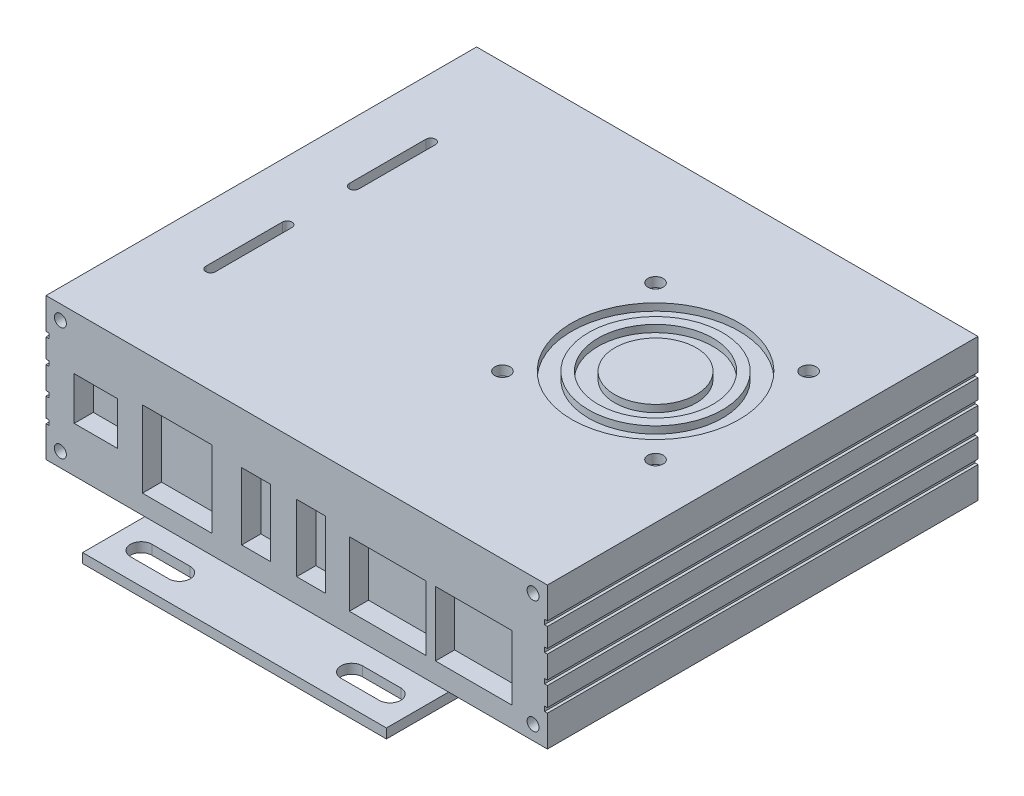
SolidWorks part; units mm, degrees
material "1060 Alloy"
ref_plane "Front Plane" through (0, 0, 0) normal (0, 0, 1) x (1, 0, 0)
ref_plane "Top Plane" through (0, 0, 0) normal (0, 1, 0) x (1, 0, 0)
ref_plane "Right Plane" through (0, 0, 0) normal (1, 0, 0) x (0, 0, -1)
sketch "Sketch1" plane through (0, 0, 0) normal (0, 1, 0) x (1, 0, 0)
  line L0 (-52.4, 45) -> (52.4, 45)
  line L1 (52.4, 45) -> (52.4, -45)
  line L2 (52.4, -45) -> (-52.4, -45)
  line L3 (-52.4, -45) -> (-52.4, 45)
extrude "Boss-Extrude1" add sketch "Sketch1" along normal blind 29.7
sketch "Sketch2" plane through (0, 0, 0) normal (0, 1, 0) x (1, 0, 0)
  line L0 (-31.75, 58) -> (31.75, 58)
  line L1 (31.75, 58) -> (31.75, -58)
  line L2 (31.75, -58) -> (-31.75, -58)
  line L3 (-31.75, -58) -> (-31.75, 58)
extrude "Boss-Extrude2" add sketch "Sketch2" against normal blind 2
sketch "Sketch3" plane through (0, -2, 0) normal (0, -1, 0) x (1, 0, 0)
  line L0 (18, 53.75) -> (26, 53.75)
  line L1 (18, 49.25) -> (26, 49.25)
  line L2 (-26, 53.75) -> (-18, 53.75)
  line L3 (-26, 49.25) -> (-18, 49.25)
  line L4 (18, -49.25) -> (26, -49.25)
  line L5 (18, -53.75) -> (26, -53.75)
  line L6 (-26, -49.25) -> (-18, -49.25)
  line L7 (-26, -53.75) -> (-18, -53.75)
  arc A0 (26, 53.75) -> (26, 49.25) centre (26, 51.5) cw
  arc A1 (18, 49.25) -> (18, 53.75) centre (18, 51.5) cw
  arc A2 (-18, 53.75) -> (-18, 49.25) centre (-18, 51.5) cw
  arc A3 (-26, 49.25) -> (-26, 53.75) centre (-26, 51.5) cw
  arc A4 (26, -49.25) -> (26, -53.75) centre (26, -51.5) cw
  arc A5 (18, -53.75) -> (18, -49.25) centre (18, -51.5) cw
  arc A6 (-18, -49.25) -> (-18, -53.75) centre (-18, -51.5) cw
  arc A7 (-26, -53.75) -> (-26, -49.25) centre (-26, -51.5) cw
extrude "Cut-Extrude1" cut sketch "Sketch3" against normal blind 3
ref_plane "Plane1" through (0, 0, 45) normal (0, 0, 1) x (1, 0, 0)
sketch "Sketch4" plane through (0, 0, 45) normal (0, 0, 1) x (1, 0, 0)
  line L0 (-46.5, 9.5) -> (-37.5, 9.5)
  line L1 (-37.5, 9.5) -> (-37.5, 18.5)
  line L2 (-37.5, 18.5) -> (-46.5, 18.5)
  line L3 (-46.5, 18.5) -> (-46.5, 9.5)
  line L4 (-32.25, 4) -> (-17.75, 4)
  line L5 (-17.75, 4) -> (-17.75, 20)
  line L6 (-17.75, 20) -> (-32.25, 20)
  line L7 (-32.25, 20) -> (-32.25, 4)
  line L8 (-11.5, 5) -> (-5.5, 5)
  line L9 (-5.5, 5) -> (-5.5, 19)
  line L10 (-5.5, 19) -> (-11.5, 19)
  line L11 (-11.5, 19) -> (-11.5, 5)
  line L12 (0, 5) -> (6, 5)
  line L13 (6, 5) -> (6, 19)
  line L14 (6, 19) -> (0, 19)
  line L15 (0, 19) -> (0, 5)
  line L16 (11, 4.25) -> (27, 4.25)
  line L17 (27, 4.25) -> (27, 17.75)
  line L18 (27, 17.75) -> (11, 17.75)
  line L19 (11, 17.75) -> (11, 4.25)
  line L20 (29, 4.25) -> (45, 4.25)
  line L21 (45, 4.25) -> (45, 17.75)
  line L22 (45, 17.75) -> (29, 17.75)
  line L23 (29, 17.75) -> (29, 4.25)
  circle A0 centre (49.4, 3) radius 1.25
  circle A1 centre (49.4, 26.7) radius 1.25
  circle A2 centre (-49.4, 3) radius 1.25
  circle A3 centre (-49.4, 26.7) radius 1.25
extrude "Cut-Extrude2" cut sketch "Sketch4" against normal blind 4
ref_plane "Plane3" through (0, 0, -45) normal (0, 0, 1) x (1, 0, 0)
sketch "Sketch5" plane through (0, 0, -45) normal (0, 0, 1) x (1, 0, 0)
  circle A0 centre (49.4, 3) radius 1.25
  circle A1 centre (49.4, 26.7) radius 1.25
  circle A2 centre (-49.4, 3) radius 1.25
  circle A3 centre (-49.4, 26.7) radius 1.25
extrude "Cut-Extrude4" cut sketch "Sketch5" along normal blind 2
ref_plane "Plane4" through (0, 29.7, 0) normal (0, 1, 0) x (1, 0, 0)
sketch "Sketch6" plane through (0, 29.7, 0) normal (0, 1, 0) x (1, 0, 0)
  circle A0 centre (25, 5) radius 17.5
  circle A1 centre (25, 5) radius 14
extrude "Cut-Extrude5" cut sketch "Sketch6" against normal blind 1.5
ref_plane "Plane5" through (0, 29.7, 0) normal (0, 1, 0) x (1, 0, 0)
sketch "Sketch7" plane through (0, 29.7, 0) normal (0, 1, 0) x (1, 0, 0)
  circle A0 centre (25, 5) radius 12
  circle A1 centre (25, 5) radius 8.5
extrude "Cut-Extrude6" cut sketch "Sketch7" against normal blind 1.5
ref_plane "Plane6" through (0, 29.7, 0) normal (0, 1, 0) x (1, 0, 0)
sketch "Sketch8" plane through (0, 29.7, 0) normal (0, 1, 0) x (1, 0, 0)
  line L0 (-39, -7) -> (-39, -23)
  line L1 (-41, -7) -> (-41, -23)
  line L2 (-39, 23) -> (-39, 7)
  line L3 (-41, 23) -> (-41, 7)
  circle A0 centre (41, -11) radius 1.6
  circle A1 centre (41, 21) radius 1.6
  circle A2 centre (9, -11) radius 1.6
  circle A3 centre (9, 21) radius 1.6
  arc A4 (-39, -23) -> (-41, -23) centre (-40, -23) cw
  arc A5 (-41, -7) -> (-39, -7) centre (-40, -7) cw
  arc A6 (-39, 7) -> (-41, 7) centre (-40, 7) cw
  arc A7 (-41, 23) -> (-39, 23) centre (-40, 23) cw
extrude "Cut-Extrude7" cut sketch "Sketch8" against normal blind 2
ref_plane "Plane7" through (52.4, 0, 0) normal (1, 0, 0) x (0, 0, -1)
sketch "Sketch9" plane through (52.4, 0, 0) normal (1, 0, 0) x (0, 0, -1)
  line L0 (45, 6.5) -> (-45, 6.5)
  line L1 (-45, 6.5) -> (-45, 7.5)
  line L2 (-45, 7.5) -> (45, 7.5)
  line L3 (45, 7.5) -> (45, 6.5)
  line L4 (45, 11.5) -> (-45, 11.5)
  line L5 (-45, 11.5) -> (-45, 12.5)
  line L6 (-45, 12.5) -> (45, 12.5)
  line L7 (45, 12.5) -> (45, 11.5)
  line L8 (45, 17.2) -> (-45, 17.2)
  line L9 (-45, 17.2) -> (-45, 18.2)
  line L10 (-45, 18.2) -> (45, 18.2)
  line L11 (45, 18.2) -> (45, 17.2)
  line L12 (45, 22.2) -> (-45, 22.2)
  line L13 (-45, 22.2) -> (-45, 23.2)
  line L14 (-45, 23.2) -> (45, 23.2)
  line L15 (45, 23.2) -> (45, 22.2)
extrude "Cut-Extrude8" cut sketch "Sketch9" against normal blind 0.6
ref_plane "Plane9" through (-52.4, 0, 0) normal (1, 0, 0) x (0, 0, -1)
sketch "Sketch10" plane through (-52.4, 0, 0) normal (1, 0, 0) x (0, 0, -1)
  line L0 (45, 6.5) -> (-45, 6.5)
  line L1 (-45, 6.5) -> (-45, 7.5)
  line L2 (-45, 7.5) -> (45, 7.5)
  line L3 (45, 7.5) -> (45, 6.5)
  line L4 (45, 11.5) -> (-45, 11.5)
  line L5 (-45, 11.5) -> (-45, 12.5)
  line L6 (-45, 12.5) -> (45, 12.5)
  line L7 (45, 12.5) -> (45, 11.5)
  line L8 (45, 17.2) -> (-45, 17.2)
  line L9 (-45, 17.2) -> (-45, 18.2)
  line L10 (-45, 18.2) -> (45, 18.2)
  line L11 (45, 18.2) -> (45, 17.2)
  line L12 (45, 22.2) -> (-45, 22.2)
  line L13 (-45, 22.2) -> (-45, 23.2)
  line L14 (-45, 23.2) -> (45, 23.2)
  line L15 (45, 23.2) -> (45, 22.2)
extrude "Cut-Extrude10" cut sketch "Sketch10" along normal blind 0.6
